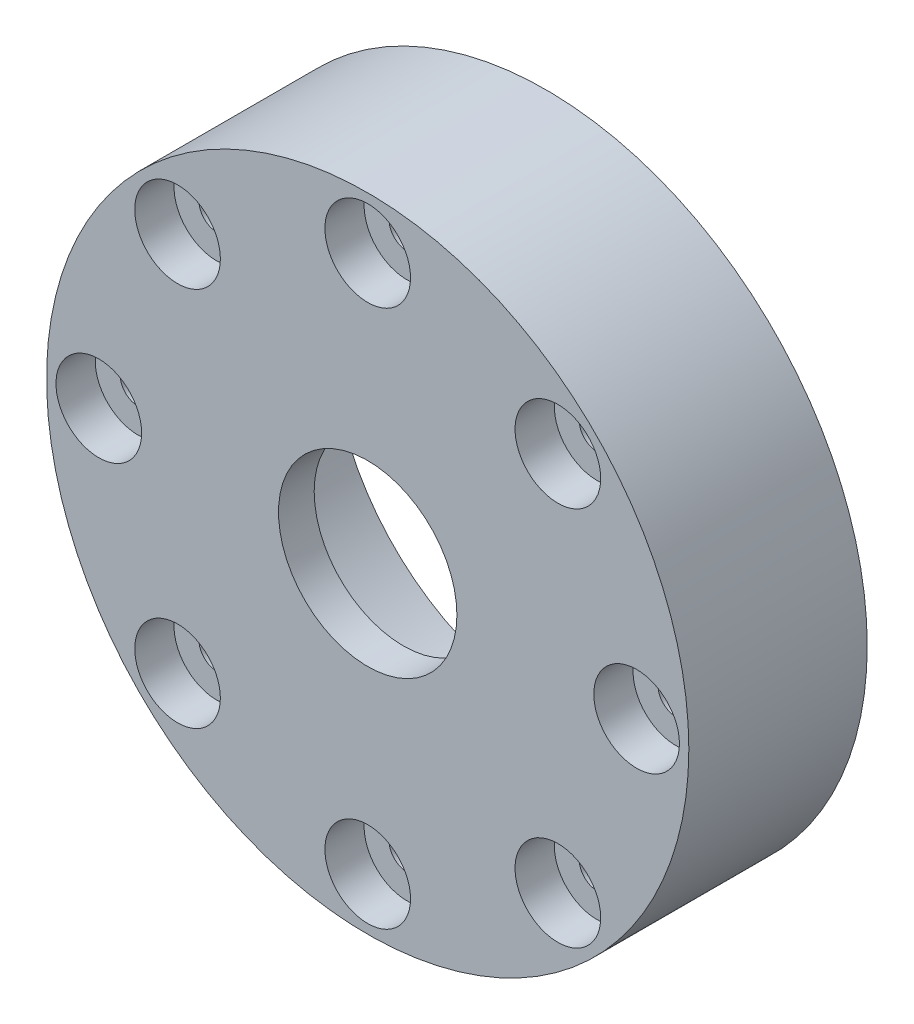
SolidWorks part; units mm, degrees
ref_plane "Спереди" through (0, 0, 0) normal (0, 0, 1) x (1, 0, 0)
ref_plane "Сверху" through (0, 0, 0) normal (0, 1, 0) x (1, 0, 0)
ref_plane "Справа" through (0, 0, 0) normal (1, 0, 0) x (0, 0, -1)
sketch "Эскиз1" plane through (0, 0, 0) normal (0, 0, 1) x (1, 0, 0)
  circle A0 centre (0, 0) radius 45
extrude "Вытянуть1" add sketch "Эскиз1" along normal blind 25
sketch "Эскиз2" plane through (0, 0, 25) normal (0, 0, 1) x (1, 0, 0)
  circle A0 centre (0, 0) radius 12.5
extrude "Вытянуть2" cut sketch "Эскиз2" against normal through all
sketch "Эскиз3" plane through (0, 0, 0) normal (0, 0, -1) x (-1, 0, 0)
  circle A0 centre (0, 0) radius 30
extrude "Вытянуть3" cut sketch "Эскиз3" against normal blind 20
sketch "Эскиз4" plane through (0, 0, 25) normal (0, 0, 1) x (1, 0, 0)
  circle A0 centre (0, 37.6835) radius 2.5
  circle A1 centre (26.6463, 26.6463) radius 2.5
  circle A2 centre (37.6835, 0) radius 2.5
  circle A3 centre (26.6463, -26.6463) radius 2.5
  circle A4 centre (0, -37.6835) radius 2.5
  circle A5 centre (-26.6463, -26.6463) radius 2.5
  circle A6 centre (-37.6835, 0) radius 2.5
  circle A7 centre (-26.6463, 26.6463) radius 2.5
extrude "Вытянуть4" cut sketch "Эскиз4" against normal through all
sketch "Эскиз6" plane through (0, 0, 25) normal (0, 0, 1) x (1, 0, 0)
  circle A0 centre (0, 37.6835) radius 6
  circle A1 centre (26.6463, 26.6463) radius 6
  circle A2 centre (37.6835, 0) radius 6
  circle A3 centre (26.6463, -26.6463) radius 6
  circle A4 centre (0, -37.6835) radius 6
  circle A5 centre (-26.6463, -26.6463) radius 6
  circle A6 centre (-37.6835, 0) radius 6
  circle A7 centre (-26.6463, 26.6463) radius 6
extrude "Вытянуть5" cut sketch "Эскиз6" against normal blind 5.5
